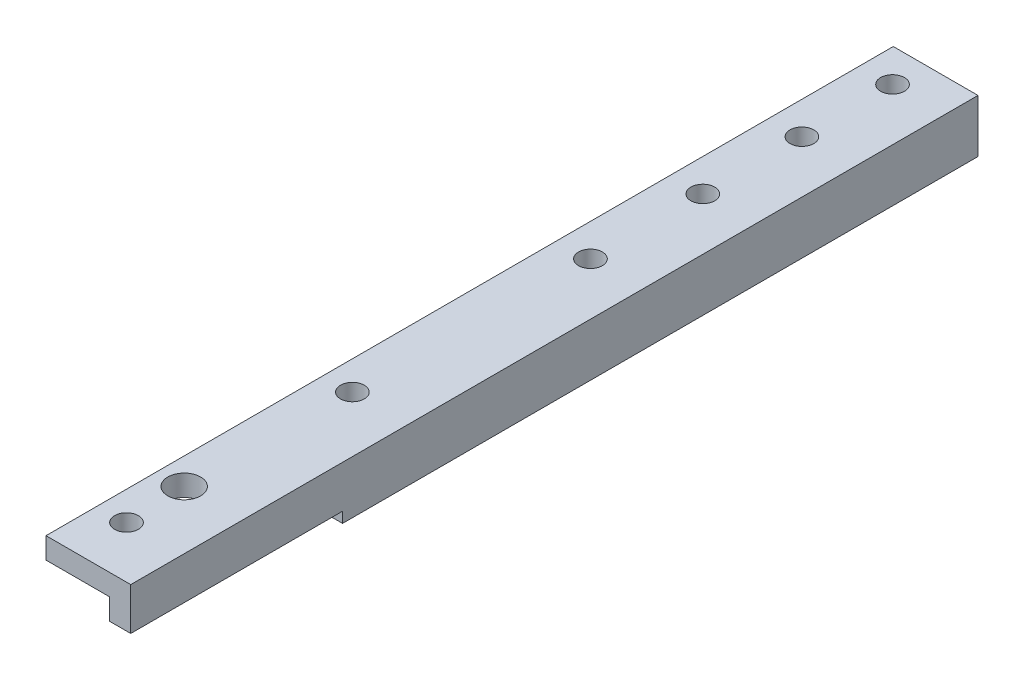
SolidWorks part; units mm, degrees
material "Plain Carbon Steel"
ref_plane "Front Plane" through (0, 0, 0) normal (0, 0, 1) x (1, 0, 0)
ref_plane "Top Plane" through (0, 0, 0) normal (0, 1, 0) x (1, 0, 0)
ref_plane "Right Plane" through (0, 0, 0) normal (1, 0, 0) x (0, 0, -1)
sketch "Sketch1" plane through (0, 0, 0) normal (0, 0, 1) x (1, 0, 0)
  line L11 (4, -4) -> (16, -4)
  line L13 (16, 0) -> (4, 0)
  line L18 (16, 0) -> (20, 0)
  line L19 (20, 0) -> (20, -10)
  line L20 (4, 0) -> (4, -4)
  line L21 (16, -4) -> (16, -10)
  line L22 (16, -10) -> (20, -10)
  point P0 (0, 0)
  dimension "D1" = 4
  dimension "D2" = 4
  dimension "D3" = 10
extrude "Boss-Extrude1" add sketch "Sketch1" along normal blind 160
sketch "Sketch2" plane through (20, 0, 0) normal (1, 0, 0) x (0, 0, -1)
  line L1 (-120, -8) -> (-160, -8)
  line L3 (-120, -10) -> (-160, -10)
  line L5 (-160, -10) -> (-160, -8)
  line L7 (-120, -10) -> (-120, -8)
  line L8 (-160, -10) -> (0, -10) construction
  line L9 (-160, -10) -> (-160, 0) construction
  point P2 (-140, -8)
  point P3 (-140.2245, -8)
  dimension "D1" = 2
  dimension "D2" = 2
  dimension "D3" = 40
extrude "Cut-Extrude1" cut sketch "Sketch2" against normal up to surface (4 mm away) up to face at (16, -7, 80)
hole_wizard "M4 Clearance Hole1" positions "Sketch3" profile "Sketch4" hole size "M4" standard "ISO" end condition through all
sketch "Sketch3" plane through (0, -4, 0) normal (0, -1, 0) x (-1, 0, 0)
  point P0 (-10.1289, -6.2673)
  point P2 (-10.1289, -23.3816)
  point P4 (-10.1289, -42.0932)
  point P6 (-10.1289, -63.3149)
  point P8 (-9.4443, -107.5838)
  point P10 (-9.4443, -150.2448)
sketch "Sketch4" plane through (10.1289, -4, 6.2673) normal (1, 0, 0) x (0, 0, -1)
  line L0 (0, 0) -> (0, 4)
  line L1 (0, 4) -> (2.25, 4)
  line L2 (2.25, 4) -> (2.25, 0)
  line L5 (2.25, 0) -> (0, 0)
  line L11 (0, -6.35) -> (0, 107.95) construction
  dimension "Thru Hole Dia." = 4.5
  dimension "Thru Hole Depth" = 4
sketch "Sketch5" plane through (0, -4, 0) normal (0, -1, 0) x (1, 0, 0)
  circle A0 centre (9, 138.8979) radius 3.1
extrude "Cut-Extrude2" cut sketch "Sketch5" against normal up to surface (7 mm away)
